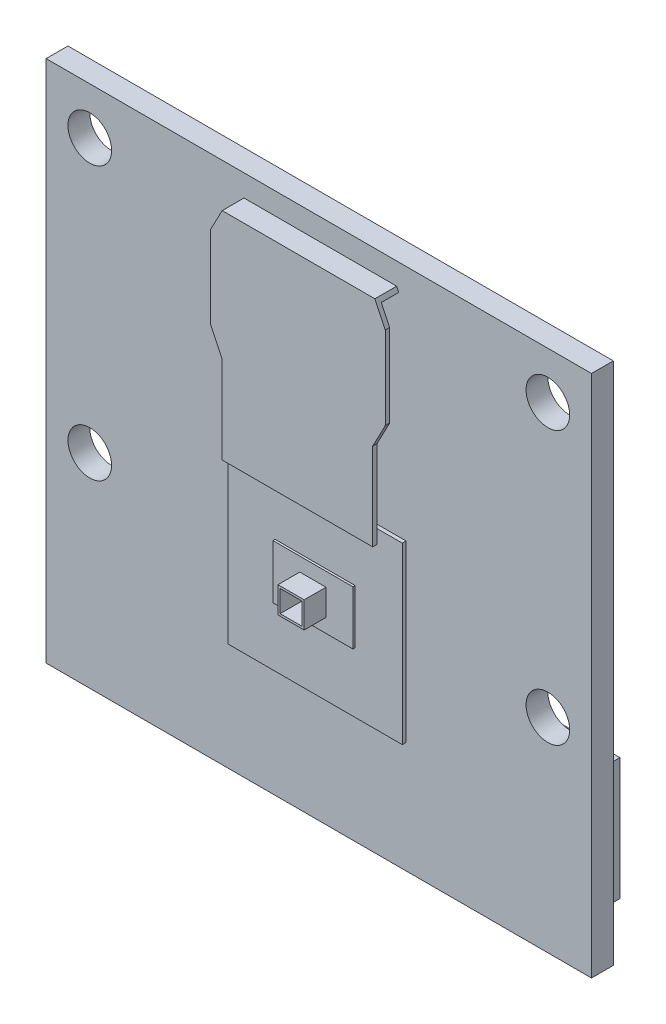
SolidWorks part; units mm, degrees
material "A-Glass Fiber"
ref_plane "Front Plane" through (0, 0, 0) normal (0, 0, 1) x (1, 0, 0)
ref_plane "Top Plane" through (0, 0, 0) normal (0, 1, 0) x (1, 0, 0)
ref_plane "Right Plane" through (0, 0, 0) normal (1, 0, 0) x (0, 0, -1)
sketch "Sketch1" plane through (0, 0, 0) normal (0, 0, 1) x (1, 0, 0)
  line L1 (-12.5, -12) -> (12.5, -12)
  line L2 (-12.5, -12) -> (-12.5, 12)
  line L3 (-12.5, 12) -> (12.5, 12)
  line L4 (12.5, -12) -> (12.5, 12)
  line L5 (-12.5, -12) -> (12.5, 12) construction
  line L6 (-12.5, 12) -> (12.5, -12) construction
  point P0 (0, 0)
  dimension "D1" = 25
  dimension "D2" = 24
extrude "Boss-Extrude1" add sketch "Sketch1" along normal blind 1
sketch "Sketch2" plane through (0, 0, 1) normal (0, 0, 1) x (1, 0, 0)
  line L0 (12.5, 12) -> (-10.5, 12) construction
  line L1 (12.5, 12) -> (-12.5, 12) construction
  line L2 (12.5, -12) -> (12.5, 9.85) construction
  line L3 (12.5, -12) -> (12.5, 12) construction
  line L4 (-12.5, -12) -> (12.5, -12) construction
  line L6 (-12.5, 12) -> (-12.5, -12) construction
  circle A0 centre (-10.5, 9.85) radius 1
  circle A1 centre (10.5, 9.85) radius 1
  circle A2 centre (10.5, -2.65) radius 1
  circle A3 centre (-10.5, -2.65) radius 1
  dimension "D3" = 2
  dimension "D6" = 2
  dimension "D8" = 2
  dimension "D10" = 2
  dimension "D1" = 23
  dimension "D2" = 21.85
  dimension "D4" = 21.85
  dimension "D5" = 23
  dimension "D7" = 2
  dimension "D9" = 9.35
  dimension "D11" = 2
  dimension "D12" = 9.35
extrude "Cut-Extrude1" cut sketch "Sketch2" against normal blind 1
sketch "Sketch3" plane through (0, 0, 1) normal (0, 0, 1) x (1, 0, 0)
  line L0 (-12.5, -12) -> (12.5, -12) construction
  line L1 (4, -6.9) -> (-4, -6.9)
  line L2 (4, -6.9) -> (4, 1.1)
  line L3 (4, 1.1) -> (-4, 1.1)
  line L4 (-4, -6.9) -> (-4, 1.1)
  line L6 (-4, -6.9) -> (4, 1.1) construction
  line L7 (-4, 1.1) -> (4, -6.9) construction
  line L9 (12.5, -12) -> (12.5, 12) construction
  point P6 (0, -2.9)
  dimension "D1" = 8
  dimension "D2" = 8
  dimension "D3" = 5.1
  dimension "D4" = 12.5
extrude "Boss-Extrude2" add sketch "Sketch3" along normal blind 5.2
sketch "Sketch4" plane through (0, 0, 6.2) normal (0, 0, 1) x (1, 0, 0)
  line L0 (-4, -6.9) -> (4, 1.1) construction
  line L1 (-4, 1.1) -> (4, -6.9) construction
  line L3 (-4, -6.9) -> (4, -6.9)
  line L4 (-4, -6.9) -> (-4, 1.1)
  line L5 (-4, 1.1) -> (4, 1.1)
  line L6 (4, -6.9) -> (4, 1.1)
  circle A0 centre (0, -2.9) radius 3.75
  dimension "D1" = 7.5
extrude "Cut-Extrude2" cut sketch "Sketch4" against normal blind 3.2
sketch "Sketch5" plane through (0, 0, 6.2) normal (0, 0, 1) x (1, 0, 0)
  circle A0 centre (0, -2.9) radius 3
  circle A1 centre (0, -2.9) radius 3.75
  dimension "D1" = 6
extrude "Cut-Extrude3" cut sketch "Sketch5" against normal blind 1.2
sketch "Sketch6" plane through (0, 0, 1) normal (0, 0, 1) x (1, 0, 0)
  line L0 (-3.4305, 1.1) -> (-3.4305, 5.1)
  line L1 (4, 1.1) -> (-4, 1.1) construction
  line L2 (-3.4305, 5.1) -> (-3.9543, 6.2)
  line L3 (-3.9543, 6.2) -> (-3.9543, 10)
  line L4 (-3.9543, 10) -> (-3.4305, 11)
  line L5 (-3.4305, 11) -> (3.5695, 11)
  line L6 (3.5695, 11) -> (4.0457, 10)
  line L7 (4.0457, 10) -> (4.0457, 6.2)
  line L8 (4.0457, 6.2) -> (3.4695, 5.1)
  line L9 (3.4695, 5.1) -> (3.4695, 1.1)
  line L10 (3.4695, 1.1) -> (-3.4305, 1.1)
  line L11 (-3.4305, 11) -> (0.0695, 11) construction
  line L12 (12.5, 12) -> (-12.5, 12) construction
  dimension "D1" = 3.8
  dimension "D2" = 3.8
  dimension "D3" = 6.9
  dimension "D4" = 4
  dimension "D5" = 4
  dimension "D6" = 7
  dimension "D7" = 3.5
  dimension "D8" = 8
  dimension "D9" = 2
  dimension "D10" = 2
  dimension "D11" = 1
extrude "Top Ribbon" add sketch "Sketch6" along normal blind 1
sketch "Sketch7" plane through (4.0457, 0, 0) normal (1, 0, 0) x (0, 0, -1)
  line L0 (-1, 10) -> (-1, 11) construction
  line L1 (-1, 10.8) -> (-1.8, 10.8)
  line L2 (-1, 10.8) -> (-1, 1.1)
  line L3 (-1, 1.1) -> (-1.8, 1.1)
  line L4 (-1.8, 10.8) -> (-1.8, 1.1)
  line L5 (-2, 1.1) -> (-1, 1.1) construction
  line L6 (-2, 11) -> (-1, 11) construction
  line L7 (-2, 6.2) -> (-2, 10) construction
  dimension "D1" = 0.2
  dimension "D2" = 0.2
extrude "Cut-Extrude4" cut sketch "Sketch7" against normal blind 9
sketch "Sketch8" plane through (0, 0, 0) normal (0, 0, -1) x (-1, 0, 0)
  line L0 (12.5, -12) -> (-12.5, -12) construction
  line L1 (-10, -12) -> (10, -12)
  line L2 (-10, -12) -> (-10, -6.4)
  line L3 (-10, -6.4) -> (10, -6.4)
  line L4 (10, -12) -> (10, -6.4)
  line L5 (12.5, 12) -> (12.5, -12) construction
  line L6 (-12.5, -12) -> (-12.5, 12) construction
  dimension "D1" = 5.6
  dimension "D2" = 2.5
  dimension "D3" = 2.5
extrude "Rear Ribbon" add sketch "Sketch8" along normal blind 2.8
sketch "Sketch9" plane through (0, 0, 3) normal (0, 0, 1) x (1, 0, 0)
  line L0 (-4, 1.1) -> (4, -6.9) construction
  line L1 (-4, 1.1) -> (4, 1.1)
  line L2 (-4, 1.1) -> (-4, -6.9)
  line L3 (-4, -6.9) -> (4, -6.9)
  line L4 (4, 1.1) -> (4, -6.9)
  line L5 (4, 1.1) -> (-4, -6.9) construction
  line L7 (-0.5, -3.4) -> (0.5, -3.4) construction
  line L8 (-0.5, -3.4) -> (-0.5, -2.4) construction
  line L9 (-0.5, -2.4) -> (0.5, -2.4) construction
  line L10 (0.5, -3.4) -> (0.5, -2.4) construction
  line L11 (-0.5, -3.4) -> (0.5, -2.4) construction
  line L12 (-0.5, -2.4) -> (0.5, -3.4) construction
  line L13 (-0.6, -3.5) -> (0.6, -3.5) construction
  line L14 (-0.6, -3.5) -> (-0.6, -2.3) construction
  line L15 (-0.6, -2.3) -> (0.6, -2.3) construction
  line L16 (0.6, -3.5) -> (0.6, -2.3) construction
  line L17 (-0.6, -3.5) -> (0.6, -2.3) construction
  line L18 (-0.6, -2.3) -> (0.6, -3.5) construction
  point P6 (0, -2.9)
  point P11 (0, -2.9)
  dimension "D1" = 1
  dimension "D2" = 1
  dimension "D3" = 0.1
extrude "Cut-Extrude5" cut sketch "Sketch9" against normal blind 1.8279 and the other way blind 10
sketch "Sketch10" plane through (0, 0, 1.1721) normal (0, 0, 1) x (1, 0, 0)
  line L0 (-4, 1.1) -> (4, -6.9) construction
  line L1 (4, -6.9) -> (4, 1.1) construction
  line L2 (4, 1.1) -> (-4, -6.9) construction
  line L4 (-1.835, -4.135) -> (1.835, -4.135)
  line L5 (-1.835, -4.135) -> (-1.835, -1.665)
  line L6 (-1.835, -1.665) -> (1.835, -1.665)
  line L7 (1.835, -4.135) -> (1.835, -1.665)
  line L8 (-1.835, -4.135) -> (1.835, -1.665) construction
  line L9 (-1.835, -1.665) -> (1.835, -4.135) construction
  point P4 (0, -2.9)
  dimension "D1" = 3.67
  dimension "D2" = 2.47
extrude "CCD" add sketch "Sketch10" along normal blind 0.1
sketch "Sketch11" plane through (0, 0, 1.1721) normal (0, 0, 1) x (1, 0, 0)
  line L0 (-4, 1.1) -> (4, -6.9) construction
  line L1 (4, -6.9) -> (4, 1.1) construction
  line L2 (4, 1.1) -> (-4, -6.9) construction
  line L4 (-0.5, -3.4) -> (0.5, -3.4)
  line L5 (-0.5, -3.4) -> (-0.5, -2.4)
  line L6 (-0.5, -2.4) -> (0.5, -2.4)
  line L7 (0.5, -3.4) -> (0.5, -2.4)
  line L8 (-0.5, -3.4) -> (0.5, -2.4) construction
  line L9 (-0.5, -2.4) -> (0.5, -3.4) construction
  line L10 (-0.6, -3.5) -> (0.6, -3.5)
  line L11 (-0.6, -3.5) -> (-0.6, -2.3)
  line L12 (-0.6, -2.3) -> (0.6, -2.3)
  line L13 (0.6, -3.5) -> (0.6, -2.3)
  line L14 (-0.6, -3.5) -> (0.6, -2.3) construction
  line L15 (-0.6, -2.3) -> (0.6, -3.5) construction
  point P4 (0, -2.9)
  point P13 (0, -2.9)
  dimension "D1" = 0.1
  dimension "D2" = 1
extrude "Telescope Alignment" add sketch "Sketch11" along normal blind 1.1
